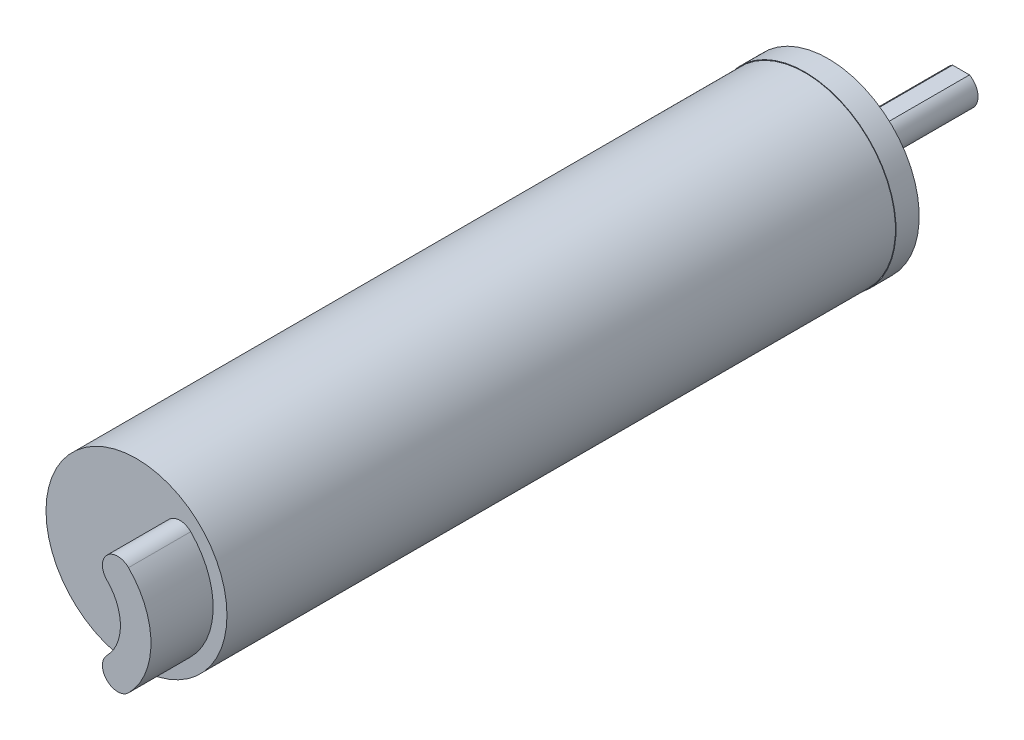
SolidWorks part; units mm, degrees
ref_plane "前视基准面" through (0, 0, 0) normal (0, 0, 1) x (1, 0, 0)
ref_plane "上视基准面" through (0, 0, 0) normal (0, 1, 0) x (1, 0, 0)
ref_plane "右视基准面" through (0, 0, 0) normal (1, 0, 0) x (0, 0, -1)
sketch "草图1" plane through (0, 0, 0) normal (0, 0, 1) x (1, 0, 0)
  circle A0 centre (0, 0) radius 8
  dimension "D1" = 16
extrude "拉伸1" add sketch "草图1" along normal blind 61.1
sketch "草图2" plane through (0, 0, 0) normal (0, 0, -1) x (-1, 0, 0)
  line L0 (-0.7483, 1.3) -> (0.7483, 1.3)
  arc A0 (-0.7483, 1.3) -> (0.7483, 1.3) centre (0, 0) ccw
  dimension "D1" = 3
  dimension "D2" = 1.3
extrude "拉伸2" add sketch "草图2" along normal blind 11.8
sketch "草图3" plane through (0, 0, 0) normal (0, 0, -1) x (-1, 0, 0)
  circle A0 centre (0, 0) radius 3
  dimension "D1" = 6
extrude "拉伸3" add sketch "草图3" along normal blind 1
sketch "草图4" plane through (0, 0, -1) normal (0, 0, -1) x (-1, 0, 0)
  circle A0 centre (0, 0) radius 2.75
  dimension "D1" = 5.5
extrude "拉伸4" add sketch "草图4" along normal blind 1.6
sketch "草图5" plane through (0, 0, 0) normal (0, 0, -1) x (-1, 0, 0)
  circle A0 centre (0, 0) radius 8.05
  dimension "D1" = 16.1
extrude "拉伸5" add sketch "草图5" against normal blind 2 and the other way blind 0.05
sketch "草图6" plane through (0, 0, -11.8) normal (0, 0, -1) x (-1, 0, 0)
  point P0 (0, 0)
sketch "草图7" plane through (0, 0, -0.05) normal (0, 0, -1) x (-1, 0, 0)
  line L0 (-5, 0) -> (5, 0)
  dimension "D1" = 10
hole_wizard "M2 螺纹孔1" positions "3D草图1" profile "草图8" tap size "M2" standard "GB"
sketch3d "3D草图1"
  point P0 (5, 0, -0.05)
  point P3 (-5, 0, -0.05)
sketch "草图8" plane through (5, 0, -0.05) normal (1, 0, 0) x (0, 1, 0)
  line L0 (0, 0) -> (0, 5.6807)
  line L1 (0, 5.6807) -> (0.8, 5.2)
  line L2 (0.8, 5.2) -> (0.8, 0)
  line L5 (0.8, 0) -> (0, 0)
  line L10 (0, 5.6807) -> (-0.8, 5.2) construction
  line L11 (0, -6.35) -> (0, 107.95) construction
  dimension "螺纹孔钻头直径" = 1.6
  dimension "螺纹孔钻头深度" = 5.2
  dimension "导头角度" = 118
cosmetic thread "孔螺蚊线1" parameters "D1"=4, "D2"=2
cosmetic thread "孔螺蚊线2" parameters "D1"=4, "D2"=2
chamfer "倒角1" distance 0.25 angle 45 2 edges at (-5.8, 0, -0.05) (4.2, 0, -0.05)
sketch "Sketch1" plane through (0, 0, -2.6) normal (0, 0, -1) x (-1, 0, 0)
  circle A0 centre (0, 0) radius 1.5
  dimension "D1" = 3
extrude "Extrude1" add sketch "Sketch1" along normal blind 1.4
sketch "Sketch2" plane through (0, 0, 61.1) normal (0, 0, 1) x (1, 0, 0)
  line L0 (0, 0) -> (3.8389, -3.8389) construction
  line L1 (0, 0) -> (5.429, 0) construction
  line L2 (0, 0) -> (3.8389, 3.8389) construction
  arc A0 (3.8389, -3.8389) -> (3.8389, 3.8389) centre (0, 0) ccw construction
  arc A1 (4.7935, -4.7935) -> (4.7935, 4.7935) centre (0, 0) ccw
  arc A2 (2.8843, -2.8843) -> (2.8843, 2.8843) centre (0, 0) ccw
  arc A3 (2.8843, -2.8843) -> (4.7935, -4.7935) centre (3.8389, -3.8389) ccw
  arc A4 (4.7935, 4.7935) -> (2.8843, 2.8843) centre (3.8389, 3.8389) ccw
  point P4 (5.429, 0)
  dimension "D2" = 1.35
  dimension "D1" = 45
extrude "Extrude2" add sketch "Sketch2" along normal blind 5.5
